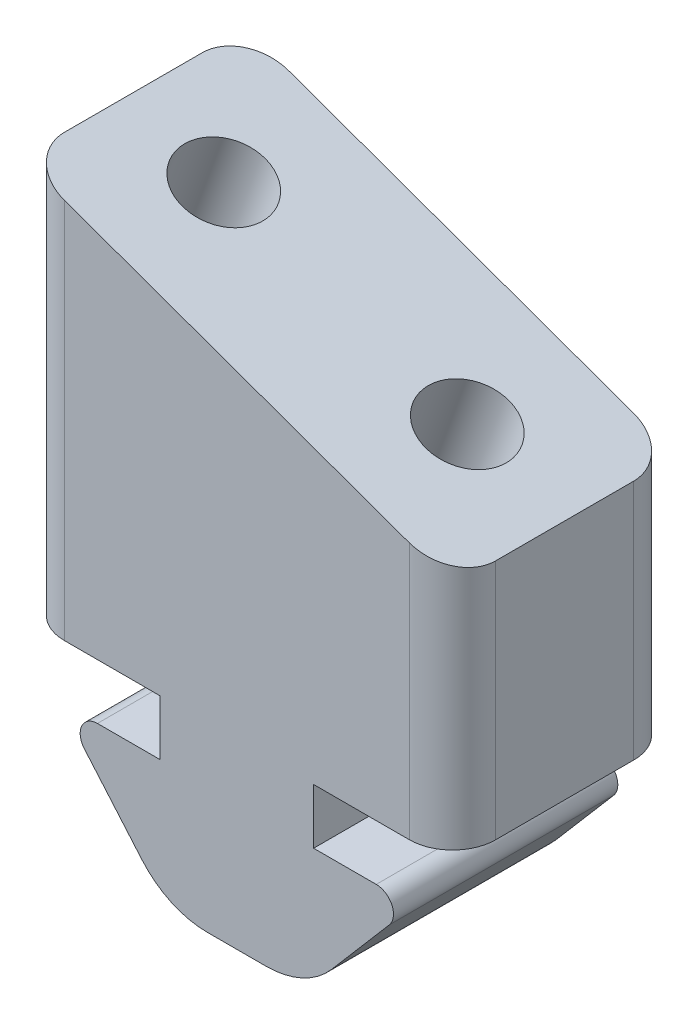
SolidWorks part; units mm, degrees
ref_plane "Front Plane" through (0, 0, 0) normal (0, 0, 1) x (1, 0, 0)
ref_plane "Top Plane" through (0, 0, 0) normal (0, 1, 0) x (1, 0, 0)
ref_plane "Right Plane" through (0, 0, 0) normal (1, 0, 0) x (0, 0, -1)
sketch "Sketch1" plane through (0, 0, 0) normal (0, 0, 1) x (1, 0, 0)
  line L0 (-4, 0) -> (4, 0)
  line L1 (4, 0) -> (10.25, 7.3)
  line L2 (10.25, 7.3) -> (4.45, 7.3)
  line L3 (4.45, 7.3) -> (4.45, 10.5)
  line L4 (4.45, 10.5) -> (-4.45, 10.5)
  line L5 (-4.45, 10.5) -> (-4.45, 7.3)
  line L6 (-4.45, 7.3) -> (-10.25, 7.3)
  line L7 (-10.25, 7.3) -> (-4, 0)
  line L9 (-12.5, 33.5) -> (12.5, 24.5)
  line L10 (-12.5, 33.5) -> (-12.5, 10.5)
  line L11 (-12.5, 10.5) -> (12.5, 10.5)
  line L12 (12.5, 24.5) -> (12.5, 10.5)
  point P0 (0, 10.5)
  point P3 (0, 23)
  point P4 (0, 0)
  point P17 (0, 29)
  point P18 (0, 23)
  dimension "D1" = 8
  dimension "D2" = 20.5
  dimension "D3" = 8.9
  dimension "D4" = 3.2
  dimension "D5" = 10.5
  dimension "D6" = 25
  dimension "D7" = 14
  dimension "D8" = 23
extrude "Boss-Extrude3" add sketch "Sketch1" along normal blind 13
fillet "Fillet1" radius 1 2 edges at (10.25, 7.3, 6.5) (-10.25, 7.3, 6.5)
fillet "Fillet2" radius 5 2 edges at (4, 0, 6.5) (-4, 0, 6.5)
sketch "Sketch2" plane through (9.2422, 25.6728, 0) normal (0.3387, 0.9409, 0) x (0.9409, -0.3387, 0)
  line L0 (-23.1082, -6.5) -> (3.4625, -6.5) construction
  line L1 (-23.1082, -13) -> (-23.1082, 0) construction
  line L2 (3.4625, -13) -> (3.4625, 0) construction
  circle A0 centre (-17.5375, -6.5) radius 2.4
  circle A1 centre (-2.5375, -6.5) radius 2.4
  dimension "D1" = 4.8
  dimension "D2" = 4.8
  dimension "D3" = 6
  dimension "D4" = 15
extrude "Cut-Extrude1" cut sketch "Sketch2" against normal blind 7.5
fillet "Fillet3" radius 2.5 4 edges at (-12.5, 22, 0) (-12.5, 22, 13) (12.5, 17.5, 0) (12.5, 17.5, 13)
equation "\"D1@Sketch2\"=\"D2@Sketch2\""
